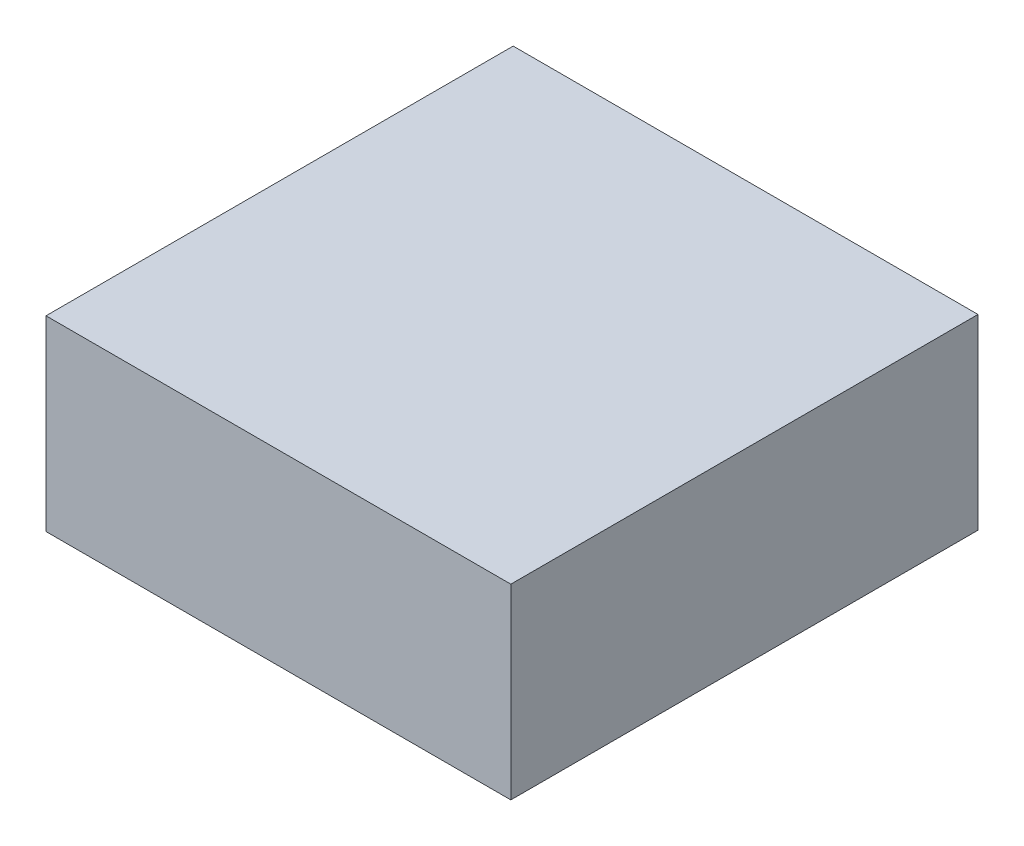
SolidWorks part; units mm, degrees
ref_plane "Plan de face" through (0, 0, 0) normal (0, 0, 1) x (1, 0, 0)
ref_plane "Plan de dessus" through (0, 0, 0) normal (0, 1, 0) x (1, 0, 0)
ref_plane "Plan de droite" through (0, 0, 0) normal (1, 0, 0) x (0, 0, -1)
sketch "Esquisse1" plane through (0, 0, 0) normal (0, 0, 1) x (1, 0, 0)
  line L1 (-9.95, 0) -> (9.95, 0)
  line L2 (-9.95, 0) -> (-9.95, 8)
  line L3 (-9.95, 8) -> (9.95, 8)
  line L4 (9.95, 0) -> (9.95, 8)
  dimension "D1" = 19.9
  dimension "D2" = 8
extrude "Boss.-Extru.1" add sketch "Esquisse1" along normal mid plane 20
